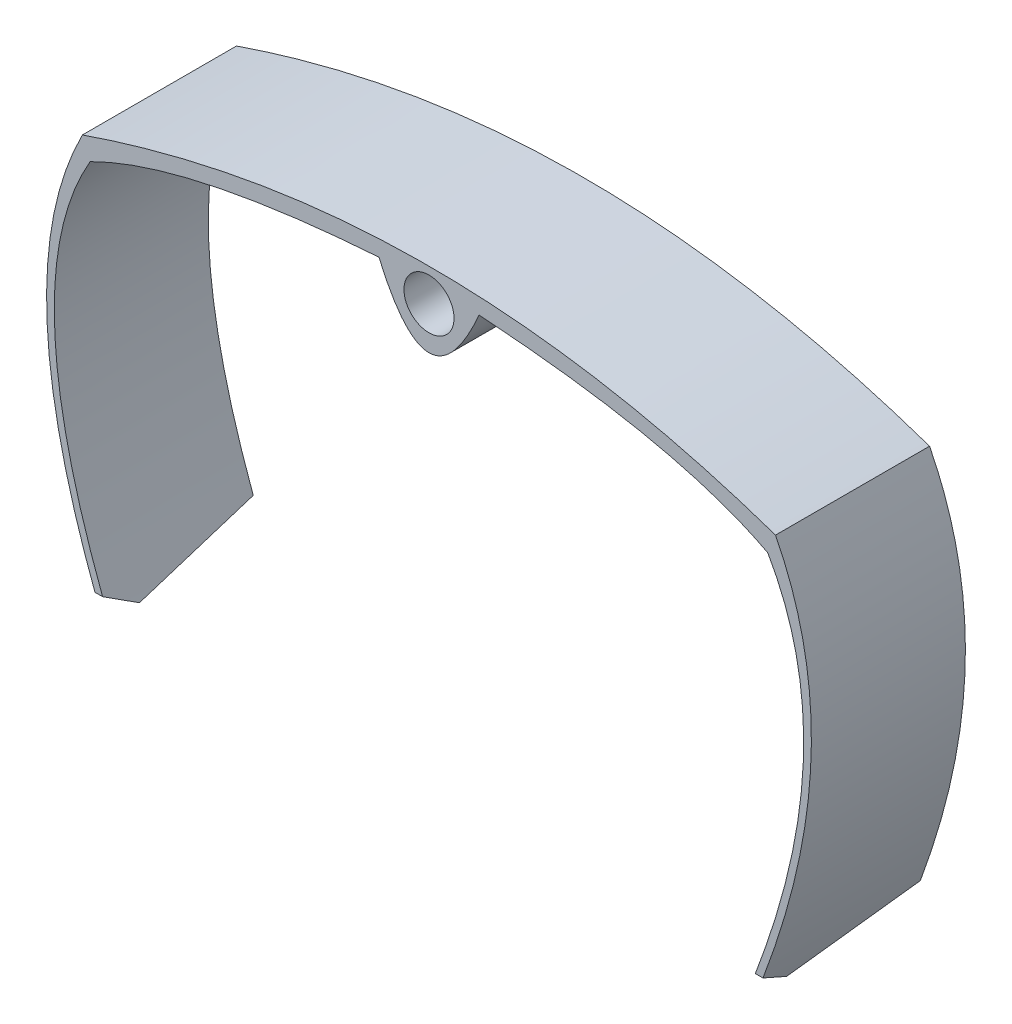
SolidWorks part; units mm, degrees
ref_plane "Front Plane" through (0, 0, 0) normal (0, 0, 1) x (1, 0, 0)
ref_plane "Top Plane" through (0, 0, 0) normal (0, 1, 0) x (1, 0, 0)
ref_plane "Right Plane" through (0, 0, 0) normal (1, 0, 0) x (0, 0, -1)
sketch "草圖1" plane through (0, 0, 0) normal (0, 0, 1) x (1, 0, 0)
  line L0 (-45, -3.5) -> (0, 12) construction
  line L1 (0, 12) -> (45, -3.5) construction
  line L4 (-6.5, 2) -> (0, -13) construction
  line L5 (0, -13) -> (6.5, 2) construction
  line L6 (6.5, 2) -> (32.2287, 0.2748) construction
  line L7 (32.2287, 0.2748) -> (44, -6) construction
  line L8 (-6.5, 2) -> (-31.608, 0.2748) construction
  line L9 (-31.608, 0.2748) -> (-44, -6) construction
  line L10 (-45, -3.5) -> (-56, -25) construction
  line L11 (-56, -25) -> (-41, -60) construction
  line L12 (45, -3.5) -> (56, -25) construction
  line L13 (56, -25) -> (41, -60) construction
  line L14 (-44, -6) -> (-55, -25) construction
  line L15 (-55, -25) -> (-40, -60) construction
  line L16 (44, -6) -> (55, -25) construction
  line L17 (55, -25) -> (40, -60) construction
  line L18 (-41, -60) -> (-40, -60)
  line L19 (40, -60) -> (41, -60)
  circle A0 centre (0, 0) radius 3.25
  spline S0 degree 2 poles (-45, -3.5) (0, 12) (45, -3.5) knots 0 0 0 1 1 1
  spline S1 degree 2 poles (-6.5, 2) (0, -13) (6.5, 2) knots 0 0 0 1 1 1
  spline S2 degree 2 poles (6.5, 2) (32.2287, 0.2748) (44, -6) knots 0 0 0 1 1 1
  spline S3 degree 2 poles (-6.5, 2) (-31.608, 0.2748) (-44, -6) knots 0 0 0 1 1 1
  spline S4 degree 2 poles (-45, -3.5) (-56, -25) (-41, -60) knots 0 0 0 1 1 1
  spline S5 degree 2 poles (45, -3.5) (56, -25) (41, -60) knots 0 0 0 1 1 1
  spline S6 degree 2 poles (-44, -6) (-55, -25) (-40, -60) knots 0 0 0 1 1 1
  spline S7 degree 2 poles (44, -6) (55, -25) (40, -60) knots 0 0 0 1 1 1
  point P23 (-32.2492, 19.3244)
  dimension "D1" = 6.5
  dimension "D2" = 90
  dimension "D3" = 45
  dimension "D4" = 12
  dimension "D5" = 1
  dimension "D6" = 13
  dimension "D7" = 6.5
  dimension "D8" = 6.5
  dimension "D9" = 32.2287
  dimension "D10" = 31.608
  dimension "D11" = 1
  dimension "D12" = 1
  dimension "D13" = 1
  dimension "D14" = 40
  dimension "D15" = 40
  dimension "D16" = 55
  dimension "D17" = 55
  dimension "D18" = 25
  dimension "D19" = 60
  dimension "D20" = 44
  dimension "D21" = 44
  dimension "D22" = 6
  dimension "D23" = 3.5
  dimension "D24" = 2
extrude "填料-伸長1" add sketch "草圖1" along normal blind 20
sketch "草圖2" plane through (0, 0, 0) normal (1, 0, 0) x (0, 0, -1)
  line L0 (-24.1346, -51.7917) -> (-16.0739, -56.3309)
  line L2 (2.0471, -71.7454) -> (-25.3018, -71.0063)
  line L3 (-25.3018, -71.0063) -> (-24.1346, -51.7917)
  line L4 (-16.0739, -56.3309) -> (-3.2255, -53.6251)
  line L5 (-3.2255, -53.6251) -> (5.975, -51.6876)
  line L6 (5.975, -51.6876) -> (8.5447, -68.5877)
  line L7 (8.5447, -68.5877) -> (2.0471, -71.7454)
extrude "除料-伸長1" cut sketch "草圖2" against normal through all and the other way through all
